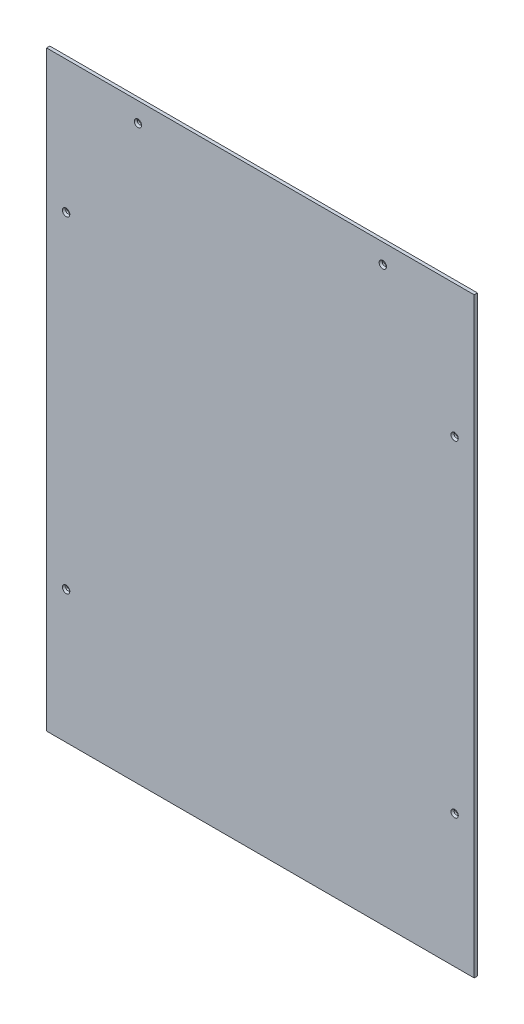
SolidWorks part; units mm, degrees
material "1.4301 (X5CrNi18-10)"
ref_plane "Plan de face" through (0, 0, 0) normal (0, 0, 1) x (1, 0, 0)
ref_plane "Plan de dessus" through (0, 0, 0) normal (0, 1, 0) x (1, 0, 0)
ref_plane "Plan de droite" through (0, 0, 0) normal (1, 0, 0) x (0, 0, -1)
sketch "Esquisse1" plane through (0, 0, 0) normal (0, 0, 1) x (1, 0, 0)
  line L1 (-262, -362.5) -> (262, -362.5)
  line L2 (-262, -362.5) -> (-262, 362.5)
  line L3 (-262, 362.5) -> (262, 362.5)
  line L4 (262, -362.5) -> (262, 362.5)
  line L5 (-262, -362.5) -> (262, 362.5) construction
  line L6 (-262, 362.5) -> (262, -362.5) construction
  point P0 (0, 0)
  dimension "D1" = 725
  dimension "D2" = 524
extrude "Boss.-Extru.1" add sketch "Esquisse1" along normal mid plane 4
sketch "Esquisse2" plane through (0, 0, 2) normal (0, 0, 1) x (1, 0, 0)
  line L0 (-262, 362.5) -> (-262, -362.5) construction
  line L1 (238, -338.5) -> (-238, -338.5) construction
  line L2 (238, -338.5) -> (238, 338.5) construction
  line L3 (238, 338.5) -> (-238, 338.5) construction
  line L4 (-238, -338.5) -> (-238, 338.5) construction
  line L5 (238, -338.5) -> (-238, 338.5) construction
  line L6 (238, 338.5) -> (-238, -338.5) construction
  line L7 (262, 362.5) -> (-262, 362.5) construction
  line L8 (-238, 0) -> (238, 0) construction
  line L9 (0, -338.5) -> (0, 338.5) construction
  circle A0 centre (-238, -200) radius 2.5
  circle A1 centre (-238, 200) radius 2.5
  circle A2 centre (238, -200) radius 2.5
  circle A3 centre (238, 200) radius 2.5
  circle A4 centre (-150, 338.5) radius 2.5
  circle A5 centre (150, 338.5) radius 2.5
  point P0 (0, 0)
  dimension "D5" = 5
  dimension "D1" = 24
  dimension "D2" = 24
  dimension "D3" = 300
  dimension "D4" = 400
extrude "Enlèv. mat.-Extru.1" cut sketch "Esquisse2" against normal through all
chamfer "Chanfrein1" distance 2 angle 45 6 edges at (240.5, -200, 2) (240.5, 200, 2) (152.5, 338.5, 2) (-147.5, 338.5, 2) (-235.5, 200, 2) (-235.5, -200, 2)
